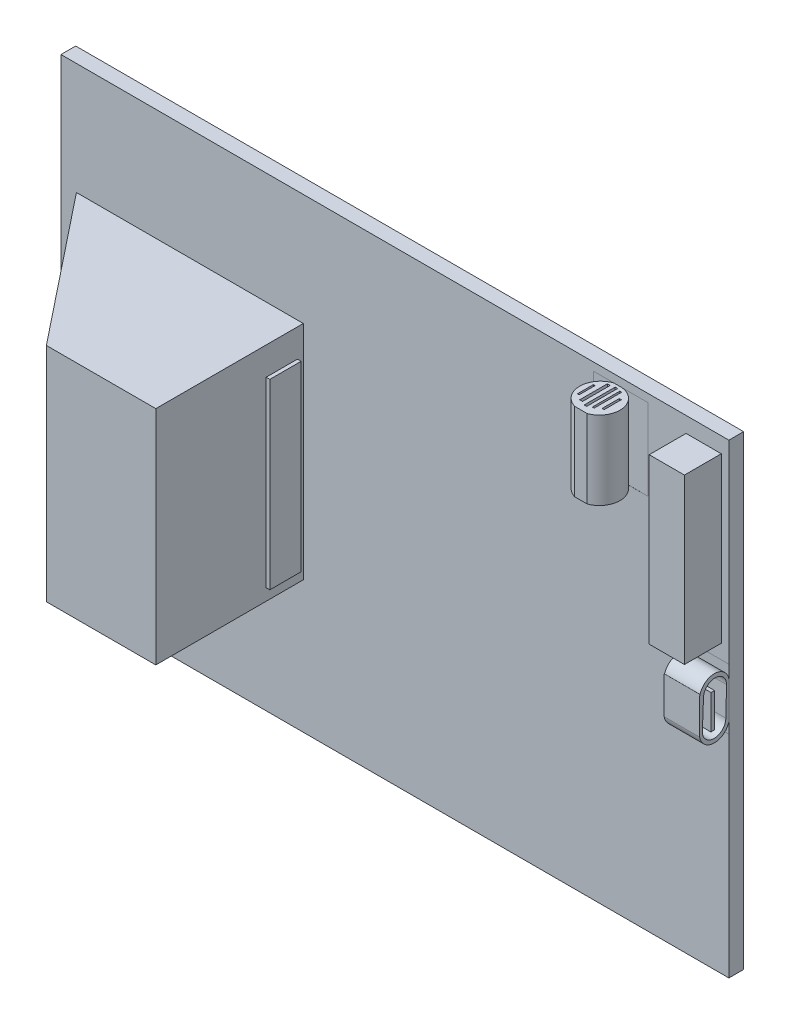
SolidWorks part; units mm, degrees
ref_plane "Front Plane" through (0, 0, 0) normal (0, 0, 1) x (1, 0, 0)
ref_plane "Top Plane" through (0, 0, 0) normal (0, 1, 0) x (1, 0, 0)
ref_plane "Right Plane" through (0, 0, 0) normal (1, 0, 0) x (0, 0, -1)
sketch "Sketch1" plane through (0, 0, 0) normal (0, 0, 1) x (1, 0, 0)
  line L1 (-83.6964, -45.2831) -> (2.5697, -45.2831)
  line L2 (-83.6964, -45.2831) -> (-83.6964, 12.5794)
  line L3 (-83.6964, 12.5794) -> (2.5697, 12.5794)
  line L4 (2.5697, -45.2831) -> (2.5697, 12.5794)
  line L5 (-83.6964, -45.2831) -> (2.5697, 12.5794) construction
  line L6 (-83.6964, 12.5794) -> (2.5697, -45.2831) construction
  point P0 (-40.5634, -16.3519)
extrude "Boss-Extrude1" add sketch "Sketch1" along normal blind 5
sketch "Sketch2" plane through (0, 0, 0) normal (0, 0, -1) x (-1, 0, 0)
  line L1 (50.5486, -38.5474) -> (14.2877, -38.5474)
  line L2 (50.5486, -38.5474) -> (50.5486, 6.6921)
  line L3 (50.5486, 6.6921) -> (14.2877, 6.6921)
  line L4 (14.2877, -38.5474) -> (14.2877, 6.6921)
  line L5 (50.5486, -38.5474) -> (14.2877, 6.6921) construction
  line L6 (50.5486, 6.6921) -> (14.2877, -38.5474) construction
  line L7 (49.8095, -37.7028) -> (15.0267, -37.7028)
  line L8 (49.8095, -37.7028) -> (49.8095, 5.8475)
  line L9 (49.8095, 5.8475) -> (15.0267, 5.8475)
  line L10 (15.0267, -37.7028) -> (15.0267, 5.8475)
  line L11 (49.8095, -37.7028) -> (15.0267, 5.8475) construction
  line L12 (49.8095, 5.8475) -> (15.0267, -37.7028) construction
  point P0 (32.4181, -15.9276)
  point P6 (32.4181, -15.9276)
extrude "Boss-Extrude2" add sketch "Sketch2" along normal blind 1
sketch "Sketch3" plane through (0, 0, 0) normal (0, 0, -1) x (-1, 0, 0)
  circle A0 centre (5.8472, -15.8094) radius 3.5601
extrude "Boss-Extrude3" add sketch "Sketch3" along normal blind 1
sketch "Sketch4" plane through (0, 0, -1) normal (0, 0, -1) x (-1, 0, 0)
  line L0 (7.4982, -13.5037) -> (7.4299, -14.2268)
  line L1 (7.3138, -18.3414) -> (7.3192, -17.6008)
  arc A0 (7.4982, -13.5037) -> (7.3138, -18.3414) centre (5.955, -15.8672) ccw
  arc A1 (7.4299, -14.2268) -> (7.3192, -17.6008) centre (5.955, -15.8672) ccw
extrude "Cut-Extrude2" cut sketch "Sketch4" against normal blind 0.5
sketch "Sketch5" plane through (0, 0, -1) normal (0, 0, -1) x (-1, 0, 0)
  line L0 (8.3401, -15.4929) -> (5.464, -15.4382)
  line L1 (8.3401, -16.1787) -> (5.464, -16.2334)
  arc A0 (8.3401, -16.1787) -> (8.3401, -15.4929) centre (8.3401, -15.8358) ccw
  arc A1 (5.464, -15.4382) -> (5.464, -16.2334) centre (5.464, -15.8358) ccw
extrude "Cut-Extrude3" cut sketch "Sketch5" against normal blind 0.5
sketch "Sketch11" plane through (0, 0, 5) normal (0, 0, 1) x (1, 0, 0)
  line L1 (-85.049, -48.3572) -> (5.5329, -48.3572)
  line L2 (-85.049, -48.3572) -> (-85.049, 14.8126)
  line L3 (-85.049, 14.8126) -> (5.5329, 14.8126)
  line L4 (5.5329, -48.3572) -> (5.5329, 14.8126)
  line L5 (-85.049, -48.3572) -> (5.5329, 14.8126) construction
  line L6 (-85.049, 14.8126) -> (5.5329, -48.3572) construction
  point P0 (-39.7581, -16.7723)
extrude "Boss-Extrude4" add sketch "Sketch11" along normal blind 2
sketch "Sketch12" plane through (2.5697, 0, 0) normal (1, 0, 0) x (0, 0, -1)
  line L0 (-5.0495, 12.5555) -> (1.3768, 8.6378)
  line L1 (1.3768, 8.6378) -> (1.4949, 17.885)
  line L2 (1.4949, 17.885) -> (-5.0495, 12.5555)
extrude "Cut-Extrude11" cut sketch "Sketch12" against normal through all
sketch "Sketch14" plane through (-85.049, 0, 0) normal (-1, 0, 0) x (0, 0, 1)
  line L0 (5, -45.2349) -> (-1.3308, -41.1782)
  line L1 (5, 12.5253) -> (5, -48.3572) construction
  line L2 (-1.3308, -41.1782) -> (-1.6233, -49.506)
  line L3 (-1.6233, -49.506) -> (5, -45.2349)
extrude "Cut-Extrude15" cut sketch "Sketch14" against normal through all
sketch "Sketch15" plane through (0, -48.3572, 0) normal (0, -1, 0) x (-1, 0, 0)
  line L0 (-2.5596, -5) -> (1.7788, 1.2395)
  line L1 (85.049, -5) -> (-5.5329, -5) construction
  line L2 (1.7788, 1.2395) -> (-4.0713, 1.1275)
  line L3 (-4.0713, 1.1275) -> (-2.5596, -5)
extrude "Cut-Extrude18" cut sketch "Sketch15" against normal through all
sketch "Sketch19" plane through (0, -48.3572, 0) normal (0, -1, 0) x (-1, 0, 0)
  line L0 (83.7172, -5) -> (87.2746, 1.6454)
  line L1 (85.049, -5) -> (-5.5329, -5) construction
  line L2 (87.2746, 1.6454) -> (78.5287, 2.7469)
  line L3 (78.5287, 2.7469) -> (83.7172, -5)
extrude "Cut-Extrude21" cut sketch "Sketch19" against normal through all
sketch "Sketch22" plane through (0, 0, 7) normal (0, 0, 1) x (1, 0, 0)
  line L1 (-82.9526, -0.3433) -> (-52.184, -0.3433)
  line L2 (-82.9526, -0.3433) -> (-82.9526, -30.4515)
  line L3 (-82.9526, -30.4515) -> (-52.184, -30.4515)
  line L4 (-52.184, -0.3433) -> (-52.184, -30.4515)
  line L5 (-82.9526, -0.3433) -> (-52.184, -30.4515) construction
  line L6 (-82.9526, -30.4515) -> (-52.184, -0.3433) construction
  point P0 (-67.5683, -15.3974)
extrude "Boss-Extrude9" add sketch "Sketch22" along normal blind 20
sketch "Sketch23" plane through (-55.4815, 0, -37.1587) normal (-0.8309, 0, -0.5565) x (-0.5565, 0, 0.8309)
  line L0 (50.7032, -28.438) -> (50.7032, -4.3391)
  line L1 (50.7032, 12.5064) -> (50.7032, -45.2151) construction
  line L2 (50.7032, -4.3391) -> (35.7393, -4.3391)
  line L3 (35.7393, -4.3391) -> (35.7393, -28.6863)
  line L4 (35.7393, -28.6863) -> (50.7032, -28.438)
extrude "Cut-Extrude25" cut sketch "Sketch23" against normal blind 30
sketch "Sketch24" plane through (0, 0, 0) normal (0, 0, -1) x (-1, 0, 0)
  line L0 (80.3685, -4.3391) -> (64.2248, -4.3391) construction
  line L1 (53.8212, -28.6863) -> (64.2248, -28.6863)
  line L2 (53.8212, -28.6863) -> (53.8212, -4.3391)
  line L3 (53.8212, -4.3391) -> (64.2248, -4.3391)
  line L4 (64.2248, -28.6863) -> (64.2248, -4.3391)
  line L5 (53.8212, -28.6863) -> (64.2248, -4.3391) construction
  line L6 (53.8212, -4.3391) -> (64.2248, -28.6863) construction
  line L7 (64.2248, -4.3391) -> (64.2248, -28.6863) construction
  point P0 (59.023, -16.5127)
extrude "Cut-Extrude27" cut sketch "Sketch24" against normal blind 7
sketch "Sketch25" plane through (0, -30.4515, 0) normal (0, -1, 0) x (-1, 0, 0)
  line L0 (67.027, -27) -> (82.9526, -7)
  line L1 (82.9526, -27) -> (52.184, -27) construction
  line L2 (82.9526, -7) -> (82.9526, -27)
  line L3 (82.9526, -27) -> (82.9526, -7) construction
  line L4 (82.9526, -27) -> (67.027, -27)
extrude "Cut-Extrude29" cut sketch "Sketch25" against normal through all
sketch "Sketch26" plane through (-28.2149, 0, 42.1276) normal (0.5565, 0, -0.8309) x (-0.8309, 0, -0.5565)
  line L0 (54.7061, -26.9497) -> (51.42, -27.0426)
  line L1 (51.42, -27.0426) -> (49.1981, -24.943)
  line L2 (49.1981, -24.943) -> (49.1134, -21.9477)
  line L3 (49.1134, -21.9477) -> (51.379, -19.9792)
  line L4 (51.379, -19.9792) -> (54.3761, -19.7757)
  line L5 (54.3761, -19.7757) -> (56.7869, -21.3756)
  line L6 (56.7869, -21.3756) -> (56.7869, -24.7523)
  line L7 (56.7869, -24.7523) -> (54.7061, -26.9497)
  line L8 (54.7061, -26.4154) -> (51.5118, -26.5172)
  line L9 (51.5118, -26.5172) -> (49.6724, -24.7913)
  line L10 (49.6724, -24.7913) -> (49.5843, -22.0272)
  line L11 (49.5843, -22.0272) -> (51.5118, -20.3421)
  line L13 (54.292, -20.113) -> (56.4421, -21.5046)
  line L14 (56.4421, -21.5046) -> (56.4421, -24.6328)
  line L15 (56.4421, -24.6328) -> (54.7061, -26.4154)
  line L16 (54.292, -20.113) -> (51.4865, -20.3421)
extrude "Boss-Extrude12" add sketch "Sketch26" along normal blind 0.5
sketch "Sketch27" plane through (-27.9367, 0, 41.7122) normal (0.5565, 0, -0.8309) x (-0.8309, 0, -0.5565)
  line L0 (54.4646, -26.3342) -> (51.6468, -26.4613)
  line L1 (51.6468, -26.4613) -> (49.7838, -24.7591)
  line L2 (49.7838, -24.7591) -> (49.7838, -22.033)
  line L3 (49.7838, -22.033) -> (51.4884, -20.6267)
  line L4 (51.4884, -20.6267) -> (54.0987, -20.567)
  line L5 (54.0987, -20.567) -> (56.1639, -21.7042)
  line L6 (56.1639, -21.7042) -> (56.2319, -24.6811)
  line L7 (56.2319, -24.6811) -> (54.4646, -26.3342)
  line L8 (54.3202, -25.7184) -> (51.7276, -25.7776)
  line L9 (51.7276, -25.7776) -> (50.5704, -24.5406)
  line L10 (50.5704, -24.5406) -> (50.4628, -22.1543)
  line L11 (50.4628, -22.1543) -> (51.4425, -21.2379)
  line L12 (51.4425, -21.2379) -> (54.0133, -21.2379)
  line L13 (54.0133, -21.2379) -> (55.475, -22.0626)
  line L14 (55.475, -22.0626) -> (55.475, -24.5406)
  line L15 (55.475, -24.5406) -> (54.3202, -25.7184)
extrude "Cut-Extrude30" cut sketch "Sketch27" against normal blind 0.5
sketch "Sketch28" plane through (-52.184, 0, 0) normal (1, 0, 0) x (0, 0, -1)
  line L1 (-7.7943, -4.1368) -> (-12.0375, -4.1368)
  line L2 (-7.7943, -4.1368) -> (-7.7943, -28.8565)
  line L3 (-7.7943, -28.8565) -> (-12.0375, -28.8565)
  line L4 (-12.0375, -4.1368) -> (-12.0375, -28.8565)
  line L5 (-7.7943, -4.1368) -> (-12.0375, -28.8565) construction
  line L6 (-7.7943, -28.8565) -> (-12.0375, -4.1368) construction
  point P0 (-9.9159, -16.4967)
extrude "Boss-Extrude13" add sketch "Sketch28" along normal blind 0.5
sketch "Sketch30" plane through (-28.2149, 0, 42.1276) normal (0.5565, 0, -0.8309) x (-0.8309, 0, -0.5565)
  line L0 (39.741, -18.4923) -> (39.4768, -15.4766)
  line L1 (39.4768, -15.4766) -> (41.6727, -13.4395)
  line L2 (41.6727, -13.4395) -> (44.994, -13.0953)
  line L3 (44.994, -13.0953) -> (47.5825, -14.9189)
  line L4 (47.5825, -14.9189) -> (47.5825, -17.5566)
  line L5 (47.5825, -17.5566) -> (45.5971, -19.8398)
  line L6 (45.5971, -19.8398) -> (42.2786, -20.1305)
  line L7 (42.2786, -20.1305) -> (39.741, -18.4923)
  line L8 (42.7534, -19.5576) -> (40.2187, -17.9152)
  line L9 (40.2187, -17.9152) -> (40.0475, -15.6187)
  line L10 (40.0475, -15.6187) -> (41.8581, -13.9959)
  line L11 (41.8581, -13.9959) -> (44.6411, -13.7001)
  line L12 (44.6411, -13.7001) -> (47.0086, -15.2342)
  line L13 (47.0086, -15.2342) -> (47.0876, -17.3469)
  line L14 (47.0876, -17.3469) -> (45.2147, -19.3741)
  line L15 (45.2147, -19.3741) -> (42.7534, -19.5576)
extrude "Boss-Extrude14" add sketch "Sketch30" along normal blind 0.5
sketch "Sketch31" plane through (-28.2149, 0, 42.1276) normal (0.5565, 0, -0.8309) x (-0.8309, 0, -0.5565)
  line L0 (42.8579, -19.0017) -> (40.9087, -17.7098)
  line L1 (40.9087, -17.7098) -> (40.7983, -15.9356)
  line L2 (40.7983, -15.9356) -> (42.2062, -14.4864)
  line L3 (42.2062, -14.4864) -> (44.0287, -14.2678)
  line L4 (44.0287, -14.2678) -> (46.1553, -15.6773)
  line L5 (46.1553, -15.6773) -> (46.2514, -17.2226)
  line L6 (46.2514, -17.2226) -> (44.5885, -18.9343)
  line L7 (44.5885, -18.9343) -> (42.8579, -19.0017)
extrude "Boss-Extrude15" add sketch "Sketch31" along normal blind 0.5
sketch "Sketch33" plane through (-28.2149, 0, 42.1276) normal (0.5565, 0, -0.8309) x (-0.8309, 0, -0.5565)
  line L0 (53.5036, -12.1793) -> (50.3513, -12.1793)
  line L1 (53.5036, -5.7866) -> (50.2502, -5.7866)
  line L2 (53.5036, -12.1793) -> (55.5149, -10.4174)
  line L3 (55.5149, -10.4174) -> (55.5149, -7.3707)
  line L4 (55.5149, -7.3707) -> (53.5036, -5.7866)
  line L5 (50.3513, -12.1793) -> (48.1508, -10.2126)
  line L6 (48.1508, -10.2126) -> (48.1508, -7.1561)
  line L7 (48.1508, -7.1561) -> (50.2502, -5.7866)
  line L8 (53.5036, -11.5928) -> (50.5381, -11.5928)
  line L9 (50.5381, -11.5928) -> (48.7427, -9.9711)
  line L10 (48.7427, -9.9711) -> (48.6105, -7.3707)
  line L11 (48.6105, -7.3707) -> (50.2502, -6.3087)
  line L12 (50.2502, -6.3087) -> (53.3239, -6.3087)
  line L13 (53.3239, -6.3087) -> (54.9664, -7.5403)
  line L14 (54.9664, -7.5403) -> (54.9664, -10.4174)
  line L15 (54.9664, -10.4174) -> (53.5036, -11.5928)
extrude "Boss-Extrude16" add sketch "Sketch33" along normal blind 0.5
sketch "Sketch34" plane through (-28.2149, 0, 42.1276) normal (0.5565, 0, -0.8309) x (-0.8309, 0, -0.5565)
  line L0 (53.1065, -10.9168) -> (50.7972, -10.9168)
  line L1 (50.7972, -10.9168) -> (49.2381, -9.7583)
  line L2 (49.2381, -9.7583) -> (49.2381, -7.7183)
  line L3 (49.2381, -7.7183) -> (50.3642, -6.7724)
  line L4 (50.3642, -6.7724) -> (52.9303, -6.7724)
  line L5 (52.9303, -6.7724) -> (54.1875, -7.7448)
  line L6 (54.1875, -7.7448) -> (54.1875, -9.9905)
  line L7 (54.1875, -9.9905) -> (53.1065, -10.9168)
extrude "Boss-Extrude17" add sketch "Sketch34" along normal blind 0.5
sketch "Sketch35" plane through (-28.2149, 0, 42.1276) normal (0.5565, 0, -0.8309) x (-0.8309, 0, -0.5565)
  line L0 (64.7134, -17.1204) -> (64.7134, -13.8698)
  line L1 (64.7134, -13.8698) -> (62.5655, -12.2617)
  line L2 (62.5655, -12.2617) -> (58.9579, -12.2617)
  line L3 (64.7134, -17.1204) -> (62.5229, -19.1048)
  line L4 (62.5229, -19.1048) -> (59.3824, -19.1048)
  line L5 (59.3824, -19.1048) -> (56.8589, -17.1993)
  line L6 (56.8589, -17.1993) -> (56.8589, -14.2019)
  line L7 (56.8589, -14.2019) -> (58.9579, -12.2617)
  line L8 (62.3869, -18.4035) -> (59.3824, -18.4035)
  line L9 (59.3824, -18.4035) -> (57.5666, -17.0465)
  line L10 (57.5666, -17.0465) -> (57.5666, -14.5319)
  line L11 (57.5666, -14.5319) -> (59.0471, -12.8652)
  line L12 (59.0471, -12.8652) -> (62.5655, -12.8652)
  line L13 (62.5655, -12.8652) -> (63.9381, -13.891)
  line L14 (63.9381, -13.891) -> (63.9381, -16.9379)
  line L15 (63.9381, -16.9379) -> (62.3869, -18.4035)
extrude "Boss-Extrude18" add sketch "Sketch35" along normal blind 0.5
sketch "Sketch36" plane through (-28.2149, 0, 42.1276) normal (0.5565, 0, -0.8309) x (-0.8309, 0, -0.5565)
  line L0 (61.8697, -17.4964) -> (59.9308, -17.4964)
  line L1 (59.9308, -17.4964) -> (58.7161, -16.6958)
  line L2 (58.7161, -16.6958) -> (58.52, -14.7296)
  line L3 (58.52, -14.7296) -> (59.3629, -13.4509)
  line L4 (59.3629, -13.4509) -> (61.6665, -13.4509)
  line L5 (61.6665, -13.4509) -> (62.906, -14.2679)
  line L6 (62.906, -14.2679) -> (62.906, -16.3755)
  line L7 (62.906, -16.3755) -> (61.8697, -17.4964)
extrude "Boss-Extrude19" add sketch "Sketch36" along normal blind 0.5
sketch "Sketch37" plane through (0, 0, 7) normal (0, 0, 1) x (1, 0, 0)
  line L1 (5.5683, -11.5042) -> (0.7589, -11.5042)
  line L2 (5.5683, -11.5042) -> (5.5683, -19.728)
  line L3 (5.5683, -19.728) -> (0.7589, -19.728)
  line L4 (0.7589, -11.5042) -> (0.7589, -19.728)
  line L5 (5.5683, -11.5042) -> (0.7589, -19.728) construction
  line L6 (5.5683, -19.728) -> (0.7589, -11.5042) construction
  point P0 (3.1636, -15.6161)
extrude "Boss-Extrude20" add sketch "Sketch37" along normal blind 4
sketch "Sketch38" plane through (5.5683, 0, 0) normal (1, 0, 0) x (0, 0, -1)
  line L2 (-11, -19.728) -> (-11, -11.5042) construction
  line L3 (-6.9987, -13.4166) -> (-7, -11.5042)
  line L4 (-11, -11.5042) -> (-7, -11.5042) construction
  line L5 (-7, -19.728) -> (-7, -11.5042) construction
  line L6 (-7, -11.5042) -> (-11, -11.5042)
  line L7 (-11, -11.5042) -> (-10.999, -13.2842)
  line L8 (-11, -18.0496) -> (-11, -19.728)
  line L9 (-11, -19.728) -> (-7, -19.728)
  line L10 (-11, -19.728) -> (-7, -19.728) construction
  line L11 (-7, -19.728) -> (-6.9992, -18.0723)
  arc A1 (-11, -18.0496) -> (-6.9992, -18.0723) centre (-8.9975, -17.692) ccw
  arc A2 (-6.9987, -13.4166) -> (-10.999, -13.2842) centre (-9.0073, -13.6054) ccw
extrude "Cut-Extrude31" cut sketch "Sketch38" against normal blind 5
sketch "Sketch39" plane through (0.7589, 0, 0) normal (-1, 0, 0) x (0, 0, 1)
  line L0 (10.9368, -12.8917) -> (11.5567, -14.0619)
  line L1 (11.5567, -14.0619) -> (12.3287, -11.916)
  line L2 (12.3287, -11.916) -> (10.8911, -11.0395)
  line L3 (10.8911, -11.0395) -> (10.9368, -12.8917)
extrude "Cut-Extrude32" cut sketch "Sketch39" against normal blind 5
sketch "Sketch40" plane through (5.5683, 0, 0) normal (1, 0, 0) x (0, 0, -1)
  line L0 (-7.3531, -13.699) -> (-7.449, -17.5958)
  line L1 (-10.478, -13.699) -> (-10.6316, -17.5208)
  arc A0 (-7.355, -13.7759) -> (-10.478, -13.699) centre (-8.9156, -13.699) ccw
  arc A1 (-10.6316, -17.5208) -> (-7.449, -17.5958) centre (-9.0412, -17.5958) ccw
extrude "Cut-Extrude33" cut sketch "Sketch40" against normal blind 4 contours L1 A1 L0 A0
sketch "Sketch41" plane through (1.5683, 0, 0) normal (1, 0, 0) x (0, 0, -1)
  line L0 (-8.9553, -13.6084) -> (-8.9553, -18.2137)
  line L1 (-8.9553, -18.2137) -> (-9.4722, -18.2137)
  line L2 (-9.4722, -18.2137) -> (-9.4722, -13.5662)
  line L3 (-9.4722, -13.5662) -> (-8.9553, -13.6084)
extrude "Boss-Extrude21" add sketch "Sketch41" along normal blind 4
sketch "Sketch42" plane through (0, 0, 7) normal (0, 0, 1) x (1, 0, 0)
  line L1 (0.7769, -13.8484) -> (-0.1485, -13.8484)
  line L2 (0.7769, -13.8484) -> (0.7769, -15.0693)
  line L3 (0.7769, -15.0693) -> (-0.1485, -15.0693)
  line L4 (-0.1485, -13.8484) -> (-0.1485, -15.0693)
  line L5 (0.7769, -13.8484) -> (-0.1485, -15.0693) construction
  line L6 (0.7769, -15.0693) -> (-0.1485, -13.8484) construction
  point P0 (0.3142, -14.4589)
extrude "Boss-Extrude22" add sketch "Sketch42" along normal blind 1
sketch "Sketch43" plane through (0, 0, 7) normal (0, 0, 1) x (1, 0, 0)
  line L1 (0.7876, -16.0237) -> (0, -16.0237)
  line L2 (0.7876, -16.0237) -> (0.7876, -17.1795)
  line L3 (0.7876, -17.1795) -> (0, -17.1795)
  line L4 (0, -16.0237) -> (0, -17.1795)
  line L5 (0.7876, -16.0237) -> (0, -17.1795) construction
  line L6 (0.7876, -17.1795) -> (0, -16.0237) construction
  point P0 (0.3938, -16.6016)
extrude "Boss-Extrude23" add sketch "Sketch43" along normal blind 1
sketch "Sketch45" plane through (0, 0, 7) normal (0, 0, 1) x (1, 0, 0)
  line L1 (-5.4203, 3.106) -> (-12.8133, 3.106)
  line L2 (-5.4203, 3.106) -> (-5.4203, 13.7297)
  line L3 (-5.4203, 13.7297) -> (-12.8133, 13.7297)
  line L4 (-12.8133, 3.106) -> (-12.8133, 13.7297)
  line L5 (-5.4203, 3.106) -> (-12.8133, 13.7297) construction
  line L6 (-5.4203, 13.7297) -> (-12.8133, 3.106) construction
  point P0 (-9.1168, 8.4178)
extrude "Boss-Extrude24" add sketch "Sketch45" along normal blind 5.4
sketch "Sketch49" plane through (0, 13.7297, 0) normal (0, 1, 0) x (1, 0, 0)
  line L4 (-9.9701, -6.9787) -> (-12.8133, -7)
  line L5 (-12.8133, -12.4) -> (-12.8133, -7) construction
  line L6 (-12.8133, -7) -> (-12.8133, -12.4)
  line L7 (-5.4203, -12.4) -> (-12.8133, -12.4) construction
  line L8 (-12.8133, -12.4) -> (-9.9877, -12.4)
  arc A0 (-9.9701, -6.9787) -> (-9.9877, -12.4) centre (-9.1757, -9.692) ccw
extrude "Cut-Extrude47" cut sketch "Sketch49" against normal blind 11
sketch "Sketch54" plane through (0, 13.7297, 0) normal (0, 1, 0) x (1, 0, 0)
  line L0 (-9.2372, -6.985) -> (-5.4203, -7)
  line L1 (-5.4203, -7) -> (-5.4203, -12.4)
  line L2 (-5.4203, -12.4) -> (-8.2825, -12.4022)
  arc A0 (-8.2825, -12.4022) -> (-9.2372, -6.985) centre (-9.2482, -9.7797) ccw
extrude "Cut-Extrude48" cut sketch "Sketch54" against normal blind 11
sketch "Sketch55" plane through (0, 13.7297, 0) normal (0, 1, 0) x (1, 0, 0)
  line L1 (-9.4942, -7.3991) -> (-9.1555, -7.3991)
  line L2 (-9.4942, -7.3991) -> (-9.4942, -11.5965)
  line L3 (-9.4942, -11.5965) -> (-9.1555, -11.5965)
  line L4 (-9.1555, -7.3991) -> (-9.1555, -11.5965)
  line L5 (-9.4942, -7.3991) -> (-9.1555, -11.5965) construction
  line L6 (-9.4942, -11.5965) -> (-9.1555, -7.3991) construction
  line L7 (-10.4091, -7.5449) -> (-10.0225, -7.5449)
  line L8 (-10.4091, -7.5449) -> (-10.4091, -11.2966)
  line L9 (-10.4091, -11.2966) -> (-10.0225, -11.2966)
  line L10 (-10.0225, -7.5449) -> (-10.0225, -11.2966)
  line L11 (-10.4091, -7.5449) -> (-10.0225, -11.2966) construction
  line L12 (-10.4091, -11.2966) -> (-10.0225, -7.5449) construction
  line L13 (-11.2656, -8.5761) -> (-11.0296, -8.5761)
  line L14 (-11.2656, -8.5761) -> (-11.2656, -10.7521)
  line L15 (-11.2656, -10.7521) -> (-11.0296, -10.7521)
  line L16 (-11.0296, -8.5761) -> (-11.0296, -10.7521)
  line L17 (-11.2656, -8.5761) -> (-11.0296, -10.7521) construction
  line L18 (-11.2656, -10.7521) -> (-11.0296, -8.5761) construction
  line L19 (-8.6997, -7.5449) -> (-8.4451, -7.5449)
  line L20 (-8.6997, -7.5449) -> (-8.6997, -11.2966)
  line L21 (-8.6997, -11.2966) -> (-8.4451, -11.2966)
  line L22 (-8.4451, -7.5449) -> (-8.4451, -11.2966)
  line L23 (-8.6997, -7.5449) -> (-8.4451, -11.2966) construction
  line L24 (-8.6997, -11.2966) -> (-8.4451, -7.5449) construction
  line L25 (-7.8715, -8.4633) -> (-7.5893, -8.4633)
  line L26 (-7.8715, -8.4633) -> (-7.8715, -10.7921)
  line L27 (-7.8715, -10.7921) -> (-7.5893, -10.7921)
  line L28 (-7.5893, -8.4633) -> (-7.5893, -10.7921)
  line L29 (-7.8715, -8.4633) -> (-7.5893, -10.7921) construction
  line L30 (-7.8715, -10.7921) -> (-7.5893, -8.4633) construction
  point P0 (-9.3248, -9.4978)
  point P5 (-10.2158, -9.4207)
  point P10 (-11.1476, -9.6641)
  point P15 (-8.5724, -9.4207)
  point P20 (-7.7304, -9.6277)
extrude "Cut-Extrude49" cut sketch "Sketch55" against normal blind 2
sketch "Sketch57" plane through (0, 0, 7) normal (0, 0, 1) x (1, 0, 0)
  line L1 (4.5041, -9.5545) -> (-0.2735, -9.5545)
  line L2 (4.5041, -9.5545) -> (4.5041, 12.6998)
  line L3 (4.5041, 12.6998) -> (-0.2735, 12.6998)
  line L4 (-0.2735, -9.5545) -> (-0.2735, 12.6998)
  line L5 (4.5041, -9.5545) -> (-0.2735, 12.6998) construction
  line L6 (4.5041, 12.6998) -> (-0.2735, -9.5545) construction
  point P0 (2.1153, 1.5727)
extrude "Boss-Extrude25" add sketch "Sketch57" along normal blind 5
